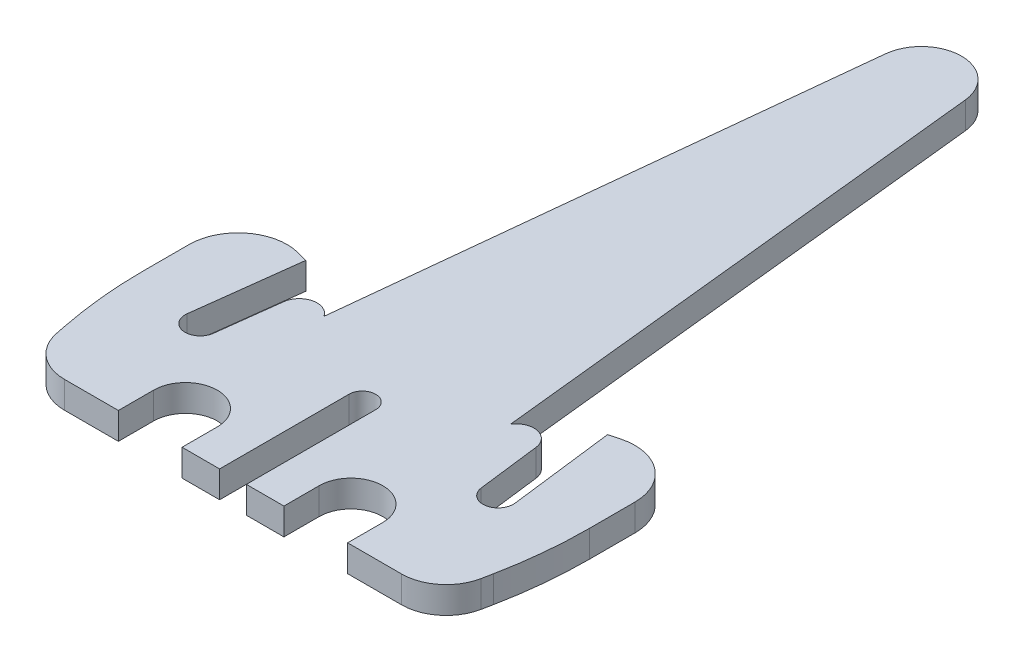
SolidWorks part; units mm, degrees
ref_plane "Front Plane" through (0, 0, 0) normal (0, 0, 1) x (1, 0, 0)
ref_plane "Top Plane" through (0, 0, 0) normal (0, 1, 0) x (1, 0, 0)
ref_plane "Right Plane" through (0, 0, 0) normal (1, 0, 0) x (0, 0, -1)
sketch "Sketch1" plane through (0, 0, 0) normal (0, 1, 0) x (1, 0, 0)
  line L0 (4.4753, 63.1404) -> (10.4632, 6.17)
  line L1 (10.4632, 6.17) -> (10.5941, 6.334)
  line L4 (16.9169, 10.5741) -> (18.0765, 10.8849)
  line L5 (25, -14.5) -> (25, 5.5723)
  line L6 (25, -14.5) -> (12.85, -14.5) construction
  line L7 (12.85, -14.5) -> (12.85, -10.55)
  line L8 (5.71, -10.55) -> (5.71, -14.5)
  line L9 (5.71, -14.5) -> (1.5, -14.5)
  line L10 (1.5, -14.5) -> (1.5, 0)
  line L11 (-1.5, 0) -> (-1.5, -14.5)
  line L12 (-1.5, -14.5) -> (-5.71, -14.5)
  line L13 (-5.71, -14.5) -> (-5.71, -10.55)
  line L14 (-12.85, -10.55) -> (-12.85, -14.5)
  line L15 (-12.85, -14.5) -> (-25, -14.5) construction
  line L16 (-25, -14.5) -> (-25, 5.5723) construction
  line L17 (-18.0765, 10.8849) -> (-16.9169, 10.5741)
  line L21 (-10.4632, 6.17) -> (-4.4753, 63.1404)
  line L22 (0, 0) -> (0, 62.67) construction
  line L23 (-24.0358, -9.3022) -> (-23.8017, -10.4772)
  line L24 (24.0358, -9.3022) -> (23.8017, -10.4772)
  line L25 (-25, 5.5723) -> (-25, 0.4696)
  line L26 (25, 0.4696) -> (25, 5.5723)
  line L27 (-18.8981, -14.5) -> (-12.85, -14.5)
  line L28 (12.85, -14.5) -> (18.8981, -14.5)
  line L29 (16.9169, 10.5741) -> (18.387, -1.2634)
  line L30 (15.013, -1.6824) -> (14.1417, 5.3325)
  line L31 (16.7, -1.4729) -> (8.6753, 63.1404) construction
  line L32 (-16.9169, 10.5741) -> (-18.387, -1.2634)
  line L33 (-15.013, -1.6824) -> (-14.1417, 5.3325)
  line L34 (-10.4632, 6.17) -> (-10.5941, 6.334)
  arc A0 (-4.4753, 63.1404) -> (4.4753, 63.1404) centre (0, 62.67) cw
  arc A1 (15.013, -1.6824) -> (18.387, -1.2634) centre (16.7, -1.4729) ccw
  arc A2 (12.85, -10.55) -> (5.71, -10.55) centre (9.28, -10.55) ccw
  arc A3 (1.5, 0) -> (-1.5, 0) centre (0, 0) ccw
  arc A4 (-5.71, -10.55) -> (-12.85, -10.55) centre (-9.28, -10.55) ccw
  arc A6 (18.0765, 10.8849) -> (25, 5.5723) centre (19.5, 5.5723) cw
  arc A7 (-25, 5.5723) -> (-18.0765, 10.8849) centre (-19.5, 5.5723) cw
  arc A8 (23.8017, -10.4772) -> (18.8981, -14.5) centre (18.8981, -9.5) cw
  arc A9 (-23.8017, -10.4772) -> (-18.8981, -14.5) centre (-18.8981, -9.5) ccw
  arc A10 (24.0358, -9.3022) -> (25, 0.4696) centre (-25, 0.4696) ccw
  arc A11 (-24.0358, -9.3022) -> (-25, 0.4696) centre (25, 0.4696) cw
  arc A14 (10.5941, 6.334) -> (14.1417, 5.3325) centre (12.157, 5.086) cw
  arc A15 (-15.013, -1.6824) -> (-18.387, -1.2634) centre (-16.7, -1.4729) cw
  arc A16 (-10.5941, 6.334) -> (-14.1417, 5.3325) centre (-12.157, 5.086) ccw
  point P15 (25, 12.74)
  point P32 (0, 58.17)
  point P33 (18.0765, -1.288)
  point P35 (0, 1.5)
  point P36 (9.28, -6.98)
  point P43 (23, -14.5)
  point P46 (-23, -14.5)
  point P56 (25, -4.4639)
  point P59 (-25, -4.4639)
  dimension "D1" = 4.5
  dimension "D6" = 1.5
  dimension "D8" = 3.57
  dimension "D14" = 72.67
  dimension "D12" = 10.5941
  dimension "D15" = 5.5
  dimension "D17" = 5
  dimension "D18" = 50
  dimension "D19" = 2
  dimension "D11" = 16.7
  dimension "D3" = 13.0271
  dimension "D20" = 1.7
  dimension "D2" = 12
  dimension "D4" = 72.67
  dimension "D5" = 50
  dimension "D7" = 16
  dimension "D9" = 7.52
  dimension "11.42" = 11.42
  dimension "D10" = 52
  dimension "D13" = 81
  dimension "D16" = 2
  dimension "D21" = 4.2
  dimension "D24" = 18.8981
extrude "Boss-Extrude1" add sketch "Sketch1" along normal blind 3
